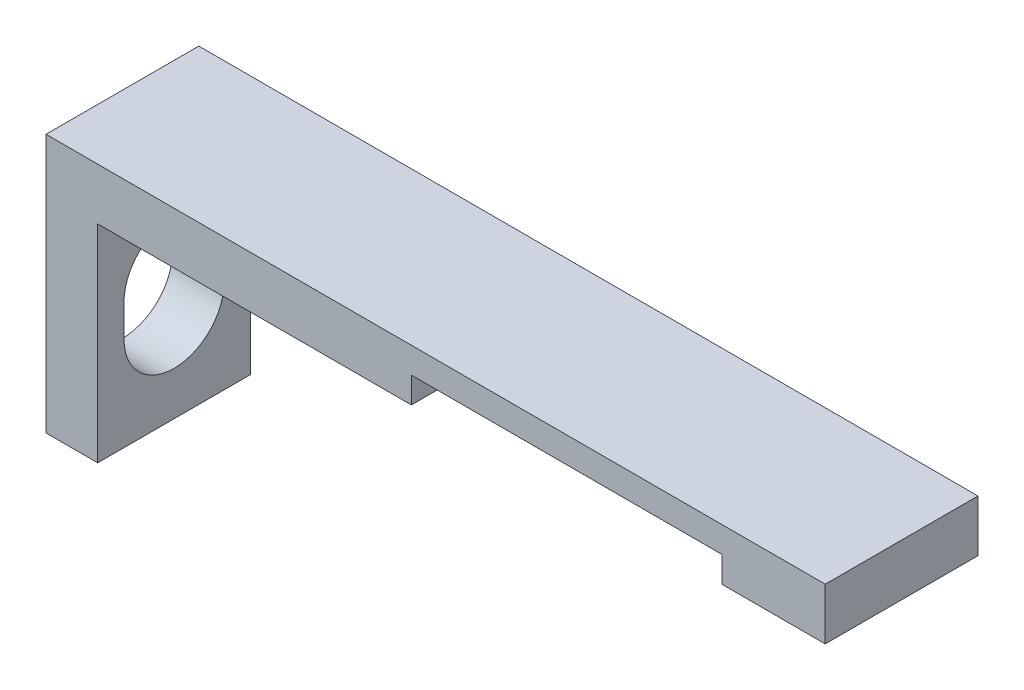
SolidWorks part; units mm, degrees
material "Plain Carbon Steel"
ref_plane "Front Plane" through (0, 0, 0) normal (0, 0, 1) x (1, 0, 0)
ref_plane "Top Plane" through (0, 0, 0) normal (0, 1, 0) x (1, 0, 0)
ref_plane "Right Plane" through (0, 0, 0) normal (1, 0, 0) x (0, 0, -1)
sketch "Sketch1" plane through (0, 0, 0) normal (0, 0, 1) x (1, 0, 0)
  line L0 (0, 0) -> (0, 16)
  line L1 (0, 16) -> (48.2, 16)
  line L2 (48.2, 16) -> (48.2, 12.8)
  line L3 (48.2, 12.8) -> (3.2, 12.8)
  line L4 (3.2, 12.8) -> (3.2, 0)
  line L5 (3.2, 0) -> (0, 0)
  dimension "D1" = 3.2
  dimension "D2" = 16
  dimension "D3" = 45
extrude "Boss-Extrude1" add sketch "Sketch1" along normal mid plane 9.45
sketch "Sketch2" plane through (0, 0, 0) normal (0, 0, 1) x (1, 0, 0)
  line L0 (3.2, 12.8) -> (48.2, 12.8) construction
  line L1 (22.6, 12.8) -> (41.8, 12.8)
  line L2 (22.6, 12.8) -> (22.6, 14.4)
  line L3 (22.6, 14.4) -> (41.8, 14.4)
  line L4 (41.8, 12.8) -> (41.8, 14.4)
  line L5 (48.2, 12.8) -> (48.2, 16) construction
  dimension "D1" = 1.6
  dimension "D2" = 6.4
  dimension "D3" = 19.2
extrude "Cut-Extrude1" cut sketch "Sketch2" along direction (0, 0, -1) on the side against the normal mid plane 9.45
sketch "Sketch3" plane through (3.2, 0, 0) normal (1, 0, 0) x (0, 0, -1)
  line L0 (0, 5.8) -> (0, 7.8) construction
  line L1 (-3.1, 5.8) -> (-3.1, 7.8)
  line L2 (3.1, 5.8) -> (3.1, 7.8)
  line L6 (-4.725, 12.8) -> (4.725, 12.8) construction
  arc A0 (-3.1, 5.8) -> (3.1, 5.8) centre (0, 5.8) ccw
  arc A1 (3.1, 7.8) -> (-3.1, 7.8) centre (0, 7.8) ccw
  circle A3 centre (0, 5.8) radius 3 construction
  point P3 (0, 6.8)
  dimension "D3" = 6
  dimension "D4" = 7
  dimension "D1" = 6.2
  dimension "D2" = 2
extrude "Cut-Extrude2" cut sketch "Sketch3" against normal up to next
